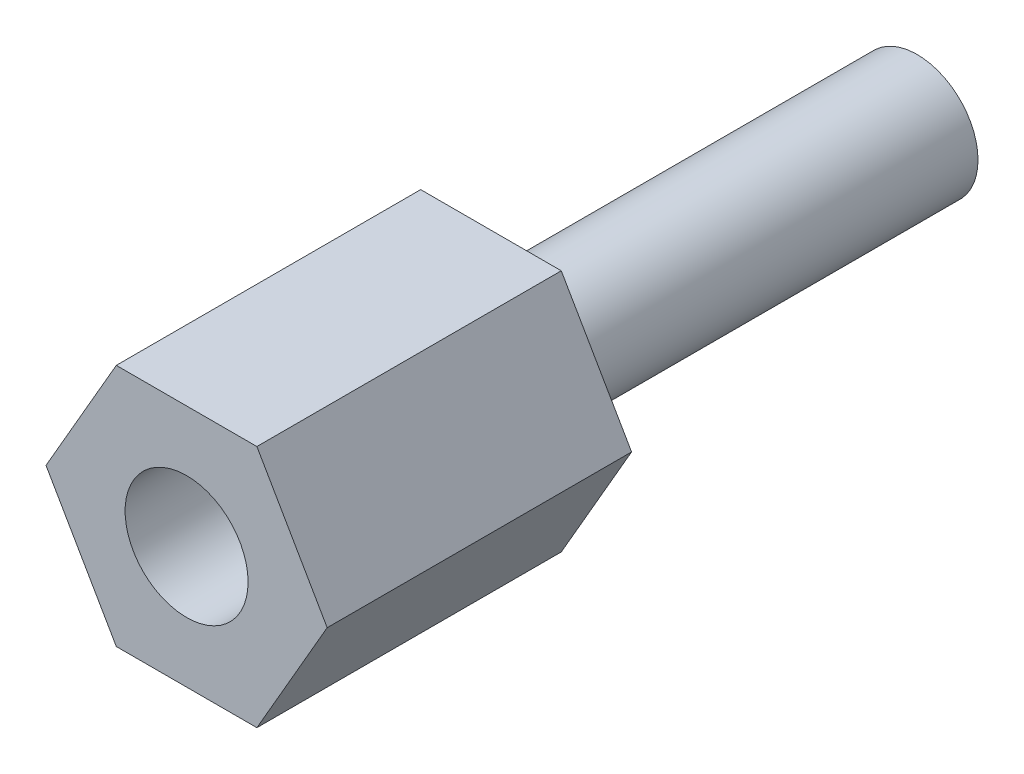
SolidWorks part; units mm, degrees
ref_plane "前视基准面" through (0, 0, 0) normal (0, 0, 1) x (1, 0, 0)
ref_plane "上视基准面" through (0, 0, 0) normal (0, 1, 0) x (1, 0, 0)
ref_plane "右视基准面" through (0, 0, 0) normal (1, 0, 0) x (0, 0, -1)
other "Configuration Table"
sketch "Female_hex_standoff_Sketch" plane through (0, 0, 0) normal (0, 0, 1) x (1, 0, 0)
  line L0 (2.3094, 0) -> (1.1547, 2)
  line L1 (1.1547, 2) -> (-1.1547, 2)
  line L2 (-1.1547, 2) -> (-2.3094, 0)
  line L3 (-2.3094, 0) -> (-1.1547, -2)
  line L4 (-1.1547, -2) -> (1.1547, -2)
  line L5 (1.1547, -2) -> (2.3094, 0)
  circle A0 centre (0, 0) radius 1.01
extrude "Female_hex_standoff" add sketch "Female_hex_standoff_Sketch" along normal blind 5 separate body
sketch "Stud_root_Sketch" plane through (0, 0, 0) normal (0, 0, 1) x (1, 0, 0)
  circle A0 centre (0, 0) radius 1.35
extrude "Stud_root" add sketch "Stud_root_Sketch" along normal blind 0.45
sketch "Male_thread_envelope_Sketch" plane through (0, 0, 0) normal (0, 0, 1) x (1, 0, 0)
  circle A0 centre (0, 0) radius 1
extrude "Male_thread_envelope" add sketch "Male_thread_envelope_Sketch" along normal blind 7 from offset 7
